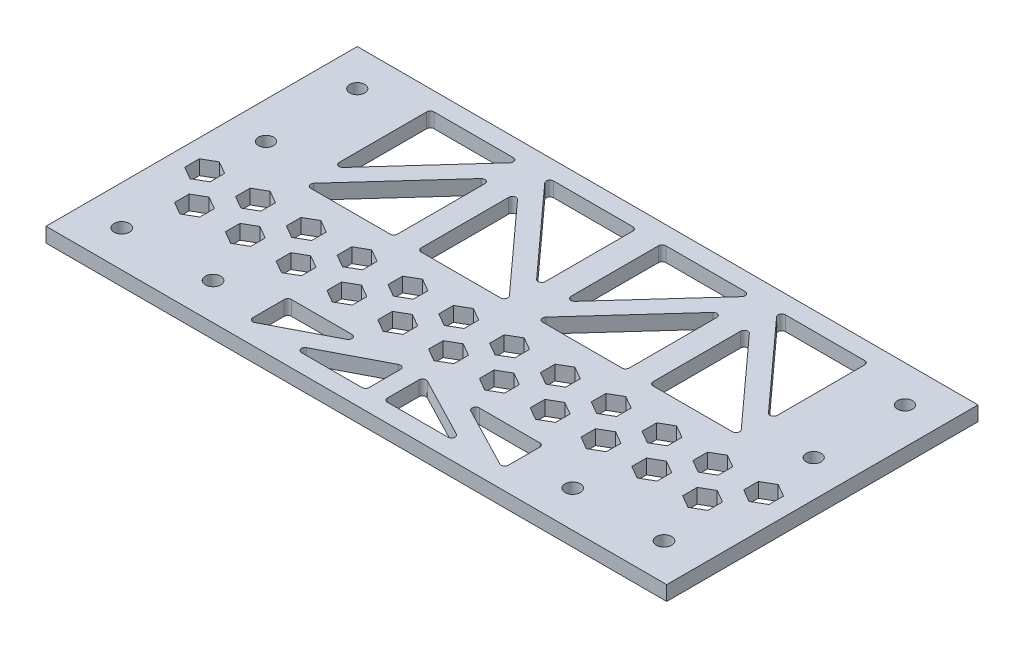
SolidWorks part; units mm, degrees
ref_plane "前视基准面" through (0, 0, 0) normal (0, 0, 1) x (1, 0, 0)
ref_plane "上视基准面" through (0, 0, 0) normal (0, 1, 0) x (1, 0, 0)
ref_plane "右视基准面" through (0, 0, 0) normal (1, 0, 0) x (0, 0, -1)
sketch "草图1" plane through (0, 0, 0) normal (0, 1, 0) x (1, 0, 0)
  line L0 (0, 0) -> (0, 85.25) construction
  line L1 (-85, 85.25) -> (85, 85.25)
  line L2 (-85, 85.25) -> (-85, 0)
  line L3 (-85, 0) -> (85, 0)
  line L4 (85, 85.25) -> (85, 0)
  line L5 (-75, 75.25) -> (-75, 50.25) construction
  line L6 (49.25, 10) -> (74.25, 10) construction
  circle A0 centre (-75, 75.25) radius 2.05
  circle A1 centre (-75, 50.25) radius 2.05
  circle A2 centre (75, 50.25) radius 2.05
  circle A3 centre (75, 75.25) radius 2.05
  circle A4 centre (74.25, 10) radius 2.1
  circle A5 centre (49.25, 10) radius 2.1
  circle A6 centre (-74.25, 10) radius 2.1
  circle A7 centre (-49.25, 10) radius 2.1
  point P4 (0, 0)
  dimension "D2" = 4.1
  dimension "D5" = 10
  dimension "D10" = 4.2
  dimension "D1" = 170
  dimension "D3" = 25
  dimension "D4" = 10
  dimension "D6" = 85.25
  dimension "D7" = 10
  dimension "D8" = 25
  dimension "D9" = 10.75
extrude "凸台-拉伸1" add sketch "草图1" along normal blind 4
sketch "草图2" plane through (0, 4, 0) normal (0, 1, 0) x (1, 0, 0)
  line L10 (-60, 80.25) -> (-35, 80.25)
  line L11 (-35, 80.25) -> (-60, 52.6917)
  line L12 (-60, 52.6917) -> (-60, 80.25)
  line L13 (85, 85.25) -> (-85, 85.25) construction
  line L14 (-85, 85.25) -> (-85, 0) construction
  line L15 (-35, 72.8083) -> (-60, 45.25)
  line L16 (-60, 45.25) -> (-35, 45.25)
  line L17 (-35, 45.25) -> (-35, 72.8083)
  line L22 (0, 0) -> (0, 79.5119) construction
  line L23 (35, 45.25) -> (35, 72.8083)
  line L24 (60, 45.25) -> (35, 45.25)
  line L25 (35, 72.8083) -> (60, 45.25)
  line L26 (60, 52.6917) -> (60, 80.25)
  line L27 (35, 80.25) -> (60, 52.6917)
  line L28 (60, 80.25) -> (35, 80.25)
  line L29 (-85, 0) -> (85, 0) construction
  line L30 (-31.75, 0) -> (-31.75, 82.5583) construction
  line L31 (31.75, 0) -> (31.75, 79.5119) construction
  line L32 (-28.5, 45.25) -> (-28.5, 72.8083)
  line L33 (-3.5, 45.25) -> (-28.5, 45.25)
  line L34 (-28.5, 72.8083) -> (-3.5, 45.25)
  line L35 (-3.5, 52.6917) -> (-3.5, 80.25)
  line L36 (-28.5, 80.25) -> (-3.5, 52.6917)
  line L37 (-3.5, 80.25) -> (-28.5, 80.25)
  line L38 (3.5, 80.25) -> (28.5, 80.25)
  line L39 (28.5, 80.25) -> (3.5, 52.6917)
  line L40 (3.5, 52.6917) -> (3.5, 80.25)
  line L41 (28.5, 72.8083) -> (3.5, 45.25)
  line L42 (3.5, 45.25) -> (28.5, 45.25)
  line L43 (28.5, 45.25) -> (28.5, 72.8083)
  dimension "D1" = 5
  dimension "D2" = 25
  dimension "D3" = 25
  dimension "D4" = 35
  dimension "D5" = 5
  dimension "D6" = 31.75
  dimension "D7" = 31.75
extrude "切除-拉伸1" cut sketch "草图2" against normal blind 10
sketch "草图4" plane through (0, 4, 0) normal (0, 1, 0) x (1, 0, 0)
  line L0 (-85, 85.25) -> (-85, 0) construction
  line L1 (-80, 33) -> (-76.5359, 31)
  line L2 (-76.5359, 31) -> (-73.0718, 33)
  line L3 (-73.0718, 33) -> (-73.0718, 37)
  line L4 (-73.0718, 37) -> (-76.5359, 39)
  line L5 (-76.5359, 39) -> (-80, 37)
  line L6 (-80, 37) -> (-80, 33)
  line L7 (-17.4093, 35) -> (-10.4219, 35) construction
  line L8 (-13.9156, 35) -> (-13.9156, 25.2436) construction
  line L9 (-13.9156, 25.2436) -> (0, 25.2436) construction
  line L10 (3.4641, 23.2436) -> (3.4641, 27.2436)
  line L11 (3.4641, 27.2436) -> (0, 29.2436)
  line L12 (0, 29.2436) -> (-3.4641, 27.2436)
  line L13 (-3.4641, 27.2436) -> (-3.4641, 23.2436)
  line L14 (-85, 0) -> (85, 0) construction
  line L15 (-66.0844, 33) -> (-62.6203, 31)
  line L16 (-62.6203, 31) -> (-59.1562, 33)
  line L17 (-59.1562, 33) -> (-59.1562, 37)
  line L18 (-59.1562, 37) -> (-62.6203, 39)
  line L19 (-62.6203, 39) -> (-66.0844, 37)
  line L20 (-66.0844, 37) -> (-66.0844, 33)
  line L21 (-52.1688, 33) -> (-48.7047, 31)
  line L22 (-48.7047, 31) -> (-45.2406, 33)
  line L23 (-45.2406, 33) -> (-45.2406, 37)
  line L24 (-45.2406, 37) -> (-48.7047, 39)
  line L25 (-48.7047, 39) -> (-52.1688, 37)
  line L26 (-52.1688, 37) -> (-52.1688, 33)
  line L27 (-38.2531, 33) -> (-34.789, 31)
  line L28 (-34.789, 31) -> (-31.3249, 33)
  line L29 (-31.3249, 33) -> (-31.3249, 37)
  line L30 (-31.3249, 37) -> (-34.789, 39)
  line L31 (-34.789, 39) -> (-38.2531, 37)
  line L32 (-38.2531, 37) -> (-38.2531, 33)
  line L33 (-24.3375, 33) -> (-20.8734, 31)
  line L34 (-20.8734, 31) -> (-17.4093, 33)
  line L35 (-17.4093, 33) -> (-17.4093, 37)
  line L36 (-17.4093, 37) -> (-20.8734, 39)
  line L37 (-20.8734, 39) -> (-24.3375, 37)
  line L38 (-24.3375, 37) -> (-24.3375, 33)
  line L39 (-10.4219, 33) -> (-6.9578, 31)
  line L40 (-6.9578, 31) -> (-3.4937, 33)
  line L41 (-3.4937, 33) -> (-3.4937, 37)
  line L42 (-3.4937, 37) -> (-6.9578, 39)
  line L43 (-6.9578, 39) -> (-10.4219, 37)
  line L44 (-10.4219, 37) -> (-10.4219, 33)
  line L45 (3.4937, 33) -> (6.9578, 31)
  line L46 (6.9578, 31) -> (10.4219, 33)
  line L47 (10.4219, 33) -> (10.4219, 37)
  line L48 (10.4219, 37) -> (6.9578, 39)
  line L49 (6.9578, 39) -> (3.4937, 37)
  line L50 (3.4937, 37) -> (3.4937, 33)
  line L51 (17.4093, 33) -> (20.8734, 31)
  line L52 (20.8734, 31) -> (24.3375, 33)
  line L53 (24.3375, 33) -> (24.3375, 37)
  line L54 (24.3375, 37) -> (20.8734, 39)
  line L55 (20.8734, 39) -> (17.4093, 37)
  line L56 (17.4093, 37) -> (17.4093, 33)
  line L57 (31.3249, 33) -> (34.789, 31)
  line L58 (34.789, 31) -> (38.2531, 33)
  line L59 (38.2531, 33) -> (38.2531, 37)
  line L60 (38.2531, 37) -> (34.789, 39)
  line L61 (34.789, 39) -> (31.3249, 37)
  line L62 (31.3249, 37) -> (31.3249, 33)
  line L63 (45.2406, 33) -> (48.7047, 31)
  line L64 (48.7047, 31) -> (52.1688, 33)
  line L65 (52.1688, 33) -> (52.1688, 37)
  line L66 (52.1688, 37) -> (48.7047, 39)
  line L67 (48.7047, 39) -> (45.2406, 37)
  line L68 (45.2406, 37) -> (45.2406, 33)
  line L69 (59.1562, 33) -> (62.6203, 31)
  line L70 (62.6203, 31) -> (66.0844, 33)
  line L71 (66.0844, 33) -> (66.0844, 37)
  line L72 (66.0844, 37) -> (62.6203, 39)
  line L73 (62.6203, 39) -> (59.1562, 37)
  line L74 (59.1562, 37) -> (59.1562, 33)
  line L75 (73.0718, 33) -> (76.5359, 31)
  line L76 (76.5359, 31) -> (80, 33)
  line L77 (80, 33) -> (80, 37)
  line L78 (80, 37) -> (76.5359, 39)
  line L79 (76.5359, 39) -> (73.0718, 37)
  line L80 (73.0718, 37) -> (73.0718, 33)
  line L99 (-3.4641, 23.2436) -> (0, 21.2436)
  line L100 (86.9874, 33) -> (90.4515, 31) [skipped]
  line L101 (90.4515, 31) -> (93.9156, 33) [skipped]
  line L102 (93.9156, 33) -> (93.9156, 37) [skipped]
  line L103 (93.9156, 37) -> (90.4515, 39) [skipped]
  line L104 (90.4515, 39) -> (86.9874, 37) [skipped]
  line L105 (86.9874, 37) -> (86.9874, 33) [skipped]
  line L106 (100.903, 33) -> (104.3671, 31) [skipped]
  line L107 (104.3671, 31) -> (107.8312, 33) [skipped]
  line L108 (107.8312, 33) -> (107.8312, 37) [skipped]
  line L109 (107.8312, 37) -> (104.3671, 39) [skipped]
  line L110 (104.3671, 39) -> (100.903, 37) [skipped]
  line L111 (100.903, 37) -> (100.903, 33) [skipped]
  line L112 (114.8187, 33) -> (118.2828, 31) [skipped]
  line L113 (118.2828, 31) -> (121.7469, 33) [skipped]
  line L114 (121.7469, 33) -> (121.7469, 37) [skipped]
  line L115 (121.7469, 37) -> (118.2828, 39) [skipped]
  line L116 (118.2828, 39) -> (114.8187, 37) [skipped]
  line L117 (114.8187, 37) -> (114.8187, 33) [skipped]
  line L118 (85, 0) -> (85, 85.25) construction
  line L119 (0, 0) -> (0, 46.2962) construction
  line L120 (0, 21.2436) -> (3.4641, 23.2436)
  line L121 (-10.4515, 23.2436) -> (-10.4515, 27.2436)
  line L122 (-10.4515, 27.2436) -> (-13.9156, 29.2436)
  line L123 (-13.9156, 29.2436) -> (-17.3797, 27.2436)
  line L124 (-17.3797, 27.2436) -> (-17.3797, 23.2436)
  line L125 (-17.3797, 23.2436) -> (-13.9156, 21.2436)
  line L126 (-13.9156, 21.2436) -> (-10.4515, 23.2436)
  line L127 (-24.3671, 23.2436) -> (-24.3671, 27.2436)
  line L128 (-24.3671, 27.2436) -> (-27.8312, 29.2436)
  line L129 (-27.8312, 29.2436) -> (-31.2953, 27.2436)
  line L130 (-31.2953, 27.2436) -> (-31.2953, 23.2436)
  line L131 (-31.2953, 23.2436) -> (-27.8312, 21.2436)
  line L132 (-27.8312, 21.2436) -> (-24.3671, 23.2436)
  line L133 (-38.2828, 23.2436) -> (-38.2828, 27.2436)
  line L134 (-38.2828, 27.2436) -> (-41.7469, 29.2436)
  line L135 (-41.7469, 29.2436) -> (-45.211, 27.2436)
  line L136 (-45.211, 27.2436) -> (-45.211, 23.2436)
  line L137 (-45.211, 23.2436) -> (-41.7469, 21.2436)
  line L138 (-41.7469, 21.2436) -> (-38.2828, 23.2436)
  line L139 (-52.1984, 23.2436) -> (-52.1984, 27.2436)
  line L140 (-52.1984, 27.2436) -> (-55.6625, 29.2436)
  line L141 (-55.6625, 29.2436) -> (-59.1266, 27.2436)
  line L142 (-59.1266, 27.2436) -> (-59.1266, 23.2436)
  line L143 (-59.1266, 23.2436) -> (-55.6625, 21.2436)
  line L144 (-55.6625, 21.2436) -> (-52.1984, 23.2436)
  line L145 (-66.114, 23.2436) -> (-66.114, 27.2436)
  line L146 (-66.114, 27.2436) -> (-69.5781, 29.2436)
  line L147 (-69.5781, 29.2436) -> (-73.0422, 27.2436)
  line L148 (-73.0422, 27.2436) -> (-73.0422, 23.2436)
  line L149 (-73.0422, 23.2436) -> (-69.5781, 21.2436)
  line L150 (-69.5781, 21.2436) -> (-66.114, 23.2436)
  line L163 (-93.9452, 23.2436) -> (-93.9452, 27.2436) [skipped]
  line L164 (-93.9452, 27.2436) -> (-97.4093, 29.2436) [skipped]
  line L165 (-97.4093, 29.2436) -> (-100.8734, 27.2436) [skipped]
  line L166 (-100.8734, 27.2436) -> (-100.8734, 23.2436) [skipped]
  line L167 (-100.8734, 23.2436) -> (-97.4093, 21.2436) [skipped]
  line L168 (-97.4093, 21.2436) -> (-93.9452, 23.2436) [skipped]
  line L169 (-80.0296, 23.2436) -> (-80.0296, 27.2436) [skipped]
  line L170 (-80.0296, 27.2436) -> (-83.4937, 29.2436) [skipped]
  line L171 (-83.4937, 29.2436) -> (-86.9578, 27.2436) [skipped]
  line L172 (-86.9578, 27.2436) -> (-86.9578, 23.2436) [skipped]
  line L173 (-86.9578, 23.2436) -> (-83.4937, 21.2436) [skipped]
  line L174 (-83.4937, 21.2436) -> (-80.0296, 23.2436) [skipped]
  line L175 (69.5781, 21.2436) -> (66.114, 23.2436)
  line L176 (73.0422, 23.2436) -> (69.5781, 21.2436)
  line L177 (73.0422, 27.2436) -> (73.0422, 23.2436)
  line L178 (69.5781, 29.2436) -> (73.0422, 27.2436)
  line L179 (66.114, 27.2436) -> (69.5781, 29.2436)
  line L180 (66.114, 23.2436) -> (66.114, 27.2436)
  line L181 (55.6625, 21.2436) -> (52.1984, 23.2436)
  line L182 (59.1266, 23.2436) -> (55.6625, 21.2436)
  line L183 (59.1266, 27.2436) -> (59.1266, 23.2436)
  line L184 (55.6625, 29.2436) -> (59.1266, 27.2436)
  line L185 (52.1984, 27.2436) -> (55.6625, 29.2436)
  line L186 (52.1984, 23.2436) -> (52.1984, 27.2436)
  line L187 (41.7469, 21.2436) -> (38.2828, 23.2436)
  line L188 (45.211, 23.2436) -> (41.7469, 21.2436)
  line L189 (45.211, 27.2436) -> (45.211, 23.2436)
  line L190 (41.7469, 29.2436) -> (45.211, 27.2436)
  line L191 (38.2828, 27.2436) -> (41.7469, 29.2436)
  line L192 (38.2828, 23.2436) -> (38.2828, 27.2436)
  line L193 (27.8312, 21.2436) -> (24.3671, 23.2436)
  line L194 (31.2953, 23.2436) -> (27.8312, 21.2436)
  line L195 (31.2953, 27.2436) -> (31.2953, 23.2436)
  line L196 (27.8312, 29.2436) -> (31.2953, 27.2436)
  line L197 (24.3671, 27.2436) -> (27.8312, 29.2436)
  line L198 (24.3671, 23.2436) -> (24.3671, 27.2436)
  line L199 (13.9156, 21.2436) -> (10.4515, 23.2436)
  line L200 (17.3797, 23.2436) -> (13.9156, 21.2436)
  line L201 (17.3797, 27.2436) -> (17.3797, 23.2436)
  line L202 (13.9156, 29.2436) -> (17.3797, 27.2436)
  line L203 (10.4515, 27.2436) -> (13.9156, 29.2436)
  line L204 (10.4515, 23.2436) -> (10.4515, 27.2436)
  circle A0 centre (-76.5359, 35) radius 3.4641 construction
  circle A1 centre (-62.6203, 35) radius 3.4641 construction
  circle A2 centre (-48.7047, 35) radius 3.4641 construction
  circle A3 centre (-34.789, 35) radius 3.4641 construction
  circle A4 centre (-20.8734, 35) radius 3.4641 construction
  circle A5 centre (-6.9578, 35) radius 3.4641 construction
  circle A6 centre (6.9578, 35) radius 3.4641 construction
  circle A7 centre (20.8734, 35) radius 3.4641 construction
  circle A8 centre (34.789, 35) radius 3.4641 construction
  circle A9 centre (48.7047, 35) radius 3.4641 construction
  circle A10 centre (62.6203, 35) radius 3.4641 construction
  circle A11 centre (76.5359, 35) radius 3.4641 construction
  circle A12 centre (0, 25.2436) radius 3.4641 construction
  circle A13 centre (-13.9156, 25.2436) radius 3.4641 construction
  circle A14 centre (-27.8312, 25.2436) radius 3.4641 construction
  circle A15 centre (90.4515, 35) radius 3.4641 construction
  circle A16 centre (104.3671, 35) radius 3.4641 construction
  circle A17 centre (118.2828, 35) radius 3.4641 construction
  circle A18 centre (-41.7469, 25.2436) radius 3.4641 construction
  circle A19 centre (-55.6625, 25.2436) radius 3.4641 construction
  circle A20 centre (-69.5781, 25.2436) radius 3.4641 construction
  circle A21 centre (69.5781, 25.2436) radius 3.4641 construction
  circle A22 centre (55.6625, 25.2436) radius 3.4641 construction
  circle A23 centre (-97.4093, 25.2436) radius 3.4641 construction
  circle A24 centre (-83.4937, 25.2436) radius 3.4641 construction
  circle A25 centre (41.7469, 25.2436) radius 3.4641 construction
  circle A26 centre (27.8312, 25.2436) radius 3.4641 construction
  circle A27 centre (13.9156, 25.2436) radius 3.4641 construction
  dimension "D1" = 4
  dimension "D2" = 5
  dimension "D3" = 35
  dimension "D5" = 5
  dimension "D6" = 4
  dimension "D7" = 5
  dimension "D4" = 15
  dimension "D8" = 8
extrude "切除-拉伸2" cut sketch "草图4" against normal blind 10
sketch "草图5" plane through (0, 4, 0) normal (0, 1, 0) x (1, 0, 0)
  line L0 (-35, 5) -> (-35, 16.2436)
  line L1 (-35, 16.2436) -> (-13.349, 16.2436)
  line L2 (-13.349, 16.2436) -> (-35, 5)
  line L3 (-24.151, 5) -> (-2.5, 5)
  line L4 (-2.5, 5) -> (-2.5, 16.2436)
  line L5 (-2.5, 16.2436) -> (-24.151, 5)
  line L6 (0, 0) -> (0, 23.0143) construction
  line L7 (-85, 0) -> (85, 0) construction
  line L10 (-85, 85.25) -> (-85, 0) construction
  line L11 (2.5, 16.2436) -> (24.151, 5)
  line L12 (2.5, 5) -> (2.5, 16.2436)
  line L13 (24.151, 5) -> (2.5, 5)
  line L14 (13.349, 16.2436) -> (35, 5)
  line L15 (35, 16.2436) -> (13.349, 16.2436)
  line L16 (35, 5) -> (35, 16.2436)
  dimension "D1" = 5
  dimension "D2" = 5
  dimension "D3" = 50
  dimension "D4" = 5
  dimension "D5" = 2.5
extrude "切除-拉伸3" cut sketch "草图5" against normal blind 10
fillet "圆角1" radius 1 36 edges at (-60, 2, -52.6917) (-60, 2, -80.25) (-35, 2, -80.25) (-60, 2, -45.25) (-35, 2, -45.25) (-35, 2, -72.8083) (60, 2, -52.6917) (35, 2, -80.25) (60, 2, -80.25) (60, 2, -45.25) (35, 2, -45.25) (35, 2, -72.8083) (3.5, 2, -45.25) (28.5, 2, -45.25) (28.5, 2, -72.8083) (28.5, 2, -80.25) (3.5, 2, -52.6917) (3.5, 2, -80.25) (-3.5, 2, -52.6917) (-28.5, 2, -80.25) (-3.5, 2, -80.25) (-3.5, 2, -45.25) (-28.5, 2, -45.25) (-28.5, 2, -72.8083) (35, 2, -5) (13.349, 2, -16.2436) (35, 2, -16.2436) (24.151, 2, -5) (2.5, 2, -5) (2.5, 2, -16.2436) (-2.5, 2, -5) (-2.5, 2, -16.2436) (-24.151, 2, -5) (-13.349, 2, -16.2436) (-35, 2, -5) (-35, 2, -16.2436)
